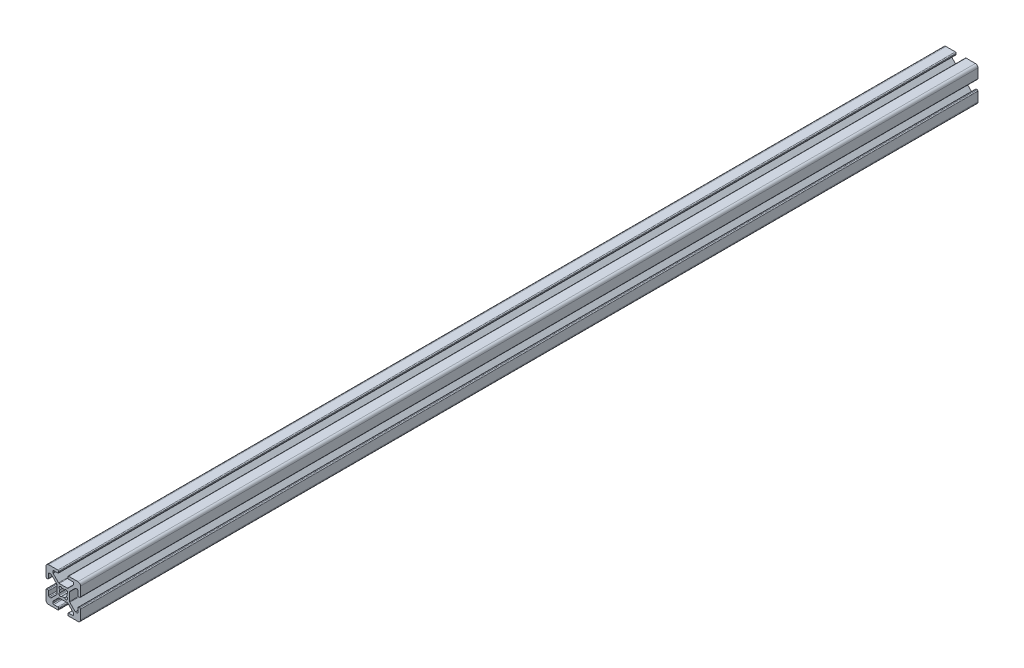
SolidWorks part; units mm, degrees
ref_plane "Front Plane" through (0, 0, 0) normal (0, 0, 1) x (1, 0, 0)
ref_plane "Top Plane" through (0, 0, 0) normal (0, 1, 0) x (1, 0, 0)
ref_plane "Right Plane" through (0, 0, 0) normal (1, 0, 0) x (0, 0, -1)
sketch "Sketch1" plane through (0, 0, 0) normal (0, 0, 1) x (1, 0, 0)
  line L0 (-5.0323, -0.3411) -> (-5.5163, -0.3411)
  line L1 (-6.0243, 0.1669) -> (-6.0243, 2.5159)
  line L2 (-4.5243, 0.1669) -> (-4.5243, 5.5289)
  line L3 (-10.8693, -5.355) -> (-10.8693, -0.5871)
  line L4 (-7.2582, 3.0239) -> (-6.5323, 3.0239)
  line L5 (-7.6174, 2.8752) -> (-10.7205, -0.2279)
  line L6 (-5.0323, -5.6011) -> (-5.5163, -5.6011)
  line L7 (-4.5243, -6.1091) -> (-4.5243, -11.4711)
  line L8 (-6.0243, -6.1091) -> (-6.0243, -8.4581)
  line L9 (-7.2582, -8.9661) -> (-6.5323, -8.9661)
  line L10 (-7.6174, -8.8173) -> (-10.7205, -5.7142)
  line L11 (-12.3994, -5.2756) -> (-12.2198, -5.096)
  line L12 (-17.1543, 6.5209) -> (-17.1543, 6.0369)
  line L13 (-17.6623, 7.0289) -> (-23.0243, 7.0289)
  line L14 (-17.6623, 5.5289) -> (-20.0113, 5.5289)
  line L15 (-12.1404, 0.6839) -> (-16.9082, 0.6839)
  line L16 (-20.5193, 4.295) -> (-20.5193, 5.0209)
  line L17 (-20.3705, 3.9358) -> (-17.2674, 0.8327)
  line L18 (-11.8943, 6.5209) -> (-11.8943, 6.0369)
  line L19 (-11.3863, 7.0289) -> (-6.0243, 7.0289)
  line L20 (-11.3863, 5.5289) -> (-9.0373, 5.5289)
  line L21 (-8.5293, 4.295) -> (-8.5293, 5.0209)
  line L22 (-8.6781, 3.9358) -> (-11.7812, 0.8327)
  line L23 (-12.2198, -0.8462) -> (-12.3994, -0.6666)
  line L24 (-24.0163, -5.6011) -> (-23.5323, -5.6011)
  line L25 (-24.5243, -6.1091) -> (-24.5243, -11.4711)
  line L26 (-23.0243, -6.1091) -> (-23.0243, -8.4581)
  line L27 (-18.1793, -0.5871) -> (-18.1793, -5.355)
  line L28 (-21.7904, -8.9661) -> (-22.5163, -8.9661)
  line L29 (-21.4312, -8.8173) -> (-18.3281, -5.7142)
  line L30 (-24.0163, -0.3411) -> (-23.5323, -0.3411)
  line L31 (-24.5243, 0.1669) -> (-24.5243, 5.5289)
  line L32 (-23.0243, 0.1669) -> (-23.0243, 2.5159)
  line L33 (-21.7904, 3.0239) -> (-22.5163, 3.0239)
  line L34 (-21.4312, 2.8752) -> (-18.3281, -0.2279)
  line L35 (-16.6492, -0.6666) -> (-16.8288, -0.8462)
  line L36 (-11.8943, -12.4631) -> (-11.8943, -11.9791)
  line L37 (-11.3863, -12.9711) -> (-6.0243, -12.9711)
  line L38 (-11.3863, -11.4711) -> (-9.0373, -11.4711)
  line L39 (-16.9082, -6.6261) -> (-12.1404, -6.6261)
  line L40 (-8.5293, -10.2371) -> (-8.5293, -10.9631)
  line L41 (-8.6781, -9.8779) -> (-11.7812, -6.7748)
  line L42 (-17.1543, -12.4631) -> (-17.1543, -11.9791)
  line L43 (-17.6623, -12.9711) -> (-23.0243, -12.9711)
  line L44 (-17.6623, -11.4711) -> (-20.0113, -11.4711)
  line L45 (-20.5193, -10.2371) -> (-20.5193, -10.9631)
  line L46 (-20.3705, -9.8779) -> (-17.2674, -6.7748)
  line L47 (-16.8288, -5.096) -> (-16.6492, -5.2756)
  arc A0 (-15.3283, -4.9062) -> (-13.7203, -4.9062) centre (-14.5243, -2.9711) ccw
  arc A1 (-6.0243, 2.5159) -> (-6.5323, 3.0239) centre (-6.5323, 2.5159) ccw
  arc A2 (-7.2582, 3.0239) -> (-7.6174, 2.8752) centre (-7.2582, 2.5159) ccw
  arc A3 (-10.7205, -0.2279) -> (-10.8693, -0.5871) centre (-10.3613, -0.5871) ccw
  arc A4 (-10.8693, -5.355) -> (-10.7205, -5.7142) centre (-10.3613, -5.355) ccw
  arc A5 (-7.6174, -8.8173) -> (-7.2582, -8.9661) centre (-7.2582, -8.4581) ccw
  arc A6 (-6.5323, -8.9661) -> (-6.0243, -8.4581) centre (-6.5323, -8.4581) ccw
  arc A7 (-5.5163, -5.6011) -> (-6.0243, -6.1091) centre (-5.5163, -6.1091) ccw
  arc A8 (-4.5243, -6.1091) -> (-5.0323, -5.6011) centre (-5.0323, -6.1091) ccw
  arc A9 (-5.0323, -0.3411) -> (-4.5243, 0.1669) centre (-5.0323, 0.1669) ccw
  arc A10 (-6.0243, 0.1669) -> (-5.5163, -0.3411) centre (-5.5163, 0.1669) ccw
  arc A11 (-13.7203, -4.9062) -> (-12.3994, -5.2756) centre (-12.9559, -4.7191) ccw
  arc A12 (-12.2198, -5.096) -> (-12.5892, -3.775) centre (-12.7763, -4.5395) ccw
  arc A13 (-17.1543, 6.5209) -> (-17.6623, 7.0289) centre (-17.6623, 6.5209) ccw
  arc A14 (-17.6623, 5.5289) -> (-17.1543, 6.0369) centre (-17.6623, 6.0369) ccw
  arc A15 (-12.5892, -3.775) -> (-12.5892, -2.1671) centre (-14.5243, -2.9711) ccw
  arc A16 (-17.2674, 0.8327) -> (-16.9082, 0.6839) centre (-16.9082, 1.1919) ccw
  arc A17 (-20.0113, 5.5289) -> (-20.5193, 5.0209) centre (-20.0113, 5.0209) ccw
  arc A18 (-20.5193, 4.295) -> (-20.3705, 3.9358) centre (-20.0113, 4.295) ccw
  arc A19 (-11.8943, 6.0369) -> (-11.3863, 5.5289) centre (-11.3863, 6.0369) ccw
  arc A20 (-11.3863, 7.0289) -> (-11.8943, 6.5209) centre (-11.3863, 6.5209) ccw
  arc A21 (-8.5293, 5.0209) -> (-9.0373, 5.5289) centre (-9.0373, 5.0209) ccw
  arc A22 (-8.6781, 3.9358) -> (-8.5293, 4.295) centre (-9.0373, 4.295) ccw
  arc A23 (-12.1404, 0.6839) -> (-11.7812, 0.8327) centre (-12.1404, 1.1919) ccw
  arc A24 (-12.5892, -2.1671) -> (-12.2198, -0.8462) centre (-12.7763, -1.4027) ccw
  arc A25 (-12.3994, -0.6666) -> (-13.7203, -1.0359) centre (-12.9559, -1.223) ccw
  arc A26 (-24.0163, -5.6011) -> (-24.5243, -6.1091) centre (-24.0163, -6.1091) ccw
  arc A27 (-23.0243, -6.1091) -> (-23.5323, -5.6011) centre (-23.5323, -6.1091) ccw
  arc A28 (-13.7203, -1.0359) -> (-15.3283, -1.0359) centre (-14.5243, -2.9711) ccw
  arc A29 (-18.3281, -5.7142) -> (-18.1793, -5.355) centre (-18.6873, -5.355) ccw
  arc A30 (-23.0243, -8.4581) -> (-22.5163, -8.9661) centre (-22.5163, -8.4581) ccw
  arc A31 (-21.7904, -8.9661) -> (-21.4312, -8.8173) centre (-21.7904, -8.4581) ccw
  arc A32 (-23.5323, -0.3411) -> (-23.0243, 0.1669) centre (-23.5323, 0.1669) ccw
  arc A33 (-24.5243, 0.1669) -> (-24.0163, -0.3411) centre (-24.0163, 0.1669) ccw
  arc A34 (-22.5163, 3.0239) -> (-23.0243, 2.5159) centre (-22.5163, 2.5159) ccw
  arc A35 (-21.4312, 2.8752) -> (-21.7904, 3.0239) centre (-21.7904, 2.5159) ccw
  arc A36 (-18.1793, -0.5871) -> (-18.3281, -0.2279) centre (-18.6873, -0.5871) ccw
  arc A37 (-15.3283, -1.0359) -> (-16.6492, -0.6666) centre (-16.0927, -1.223) ccw
  arc A38 (-16.8288, -0.8462) -> (-16.4594, -2.1671) centre (-16.2723, -1.4027) ccw
  arc A39 (-11.8943, -12.4631) -> (-11.3863, -12.9711) centre (-11.3863, -12.4631) ccw
  arc A40 (-11.3863, -11.4711) -> (-11.8943, -11.9791) centre (-11.3863, -11.9791) ccw
  arc A41 (-16.4594, -2.1671) -> (-16.4594, -3.775) centre (-14.5243, -2.9711) ccw
  arc A42 (-11.7812, -6.7748) -> (-12.1404, -6.6261) centre (-12.1404, -7.1341) ccw
  arc A43 (-9.0373, -11.4711) -> (-8.5293, -10.9631) centre (-9.0373, -10.9631) ccw
  arc A44 (-8.5293, -10.2371) -> (-8.6781, -9.8779) centre (-9.0373, -10.2371) ccw
  arc A45 (-17.1543, -11.9791) -> (-17.6623, -11.4711) centre (-17.6623, -11.9791) ccw
  arc A46 (-17.6623, -12.9711) -> (-17.1543, -12.4631) centre (-17.6623, -12.4631) ccw
  arc A47 (-20.5193, -10.9631) -> (-20.0113, -11.4711) centre (-20.0113, -10.9631) ccw
  arc A48 (-20.3705, -9.8779) -> (-20.5193, -10.2371) centre (-20.0113, -10.2371) ccw
  arc A49 (-16.9082, -6.6261) -> (-17.2674, -6.7748) centre (-16.9082, -7.1341) ccw
  arc A50 (-16.4594, -3.775) -> (-16.8288, -5.096) centre (-16.2723, -4.5395) ccw
  arc A51 (-16.6492, -5.2756) -> (-15.3283, -4.9062) centre (-16.0927, -4.7191) ccw
  arc A52 (-4.5243, 5.5289) -> (-6.0243, 7.0289) centre (-6.0243, 5.5289) ccw
  arc A53 (-6.0243, -12.9711) -> (-4.5243, -11.4711) centre (-6.0243, -11.4711) ccw
  arc A54 (-24.5243, -11.4711) -> (-23.0243, -12.9711) centre (-23.0243, -11.4711) ccw
  arc A55 (-23.0243, 7.0289) -> (-24.5243, 5.5289) centre (-23.0243, 5.5289) ccw
extrude "Extrude1" add sketch "Sketch1" along normal blind 520
